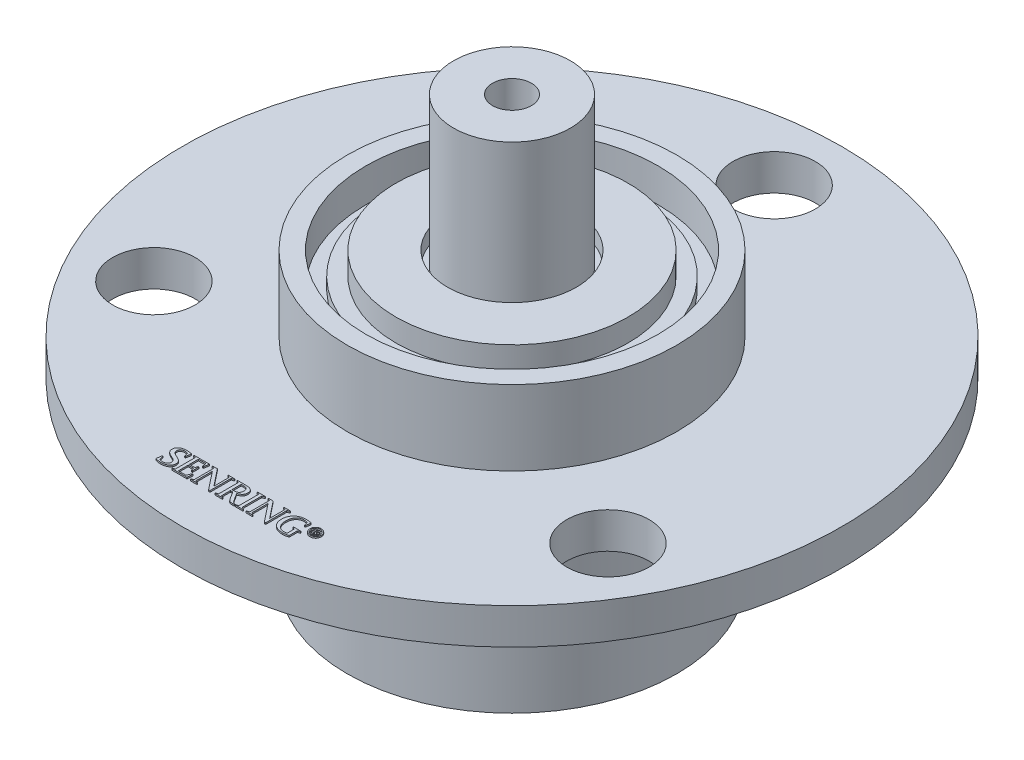
SolidWorks part; units mm, degrees
ref_plane "Front Plane" through (0, 0, 0) normal (0, 0, 1) x (1, 0, 0)
ref_plane "Top Plane" through (0, 0, 0) normal (0, 1, 0) x (1, 0, 0)
ref_plane "Right Plane" through (0, 0, 0) normal (1, 0, 0) x (0, 0, -1)
sketch "Sketch1" plane through (0, 0, 0) normal (0, 1, 0) x (1, 0, 0)
  circle A0 centre (0, 0) radius 22
  dimension "D1" = 44
extrude "Boss-Extrude1" add sketch "Sketch1" along normal blind 2.4
sketch "Sketch2" plane through (0, 2.4, 0) normal (0, 1, 0) x (1, 0, 0)
  circle A0 centre (0, 0) radius 11
  dimension "D1" = 22
extrude "Boss-Extrude2" add sketch "Sketch2" along normal blind 5
sketch "Sketch3" plane through (0, 0, 0) normal (0, -1, 0) x (1, 0, 0)
  circle A0 centre (0, 0) radius 11
  circle A1 centre (0, 0) radius 11 construction
extrude "Boss-Extrude3" add sketch "Sketch3" along normal blind 11.6
sketch "Sketch4" plane through (0, 2.4, 0) normal (0, 1, 0) x (1, 0, 0)
  circle A0 centre (0, 0) radius 17.5 construction
  circle A1 centre (0, 17.5) radius 2.75
  circle A2 centre (15.1554, -8.75) radius 2.75
  circle A3 centre (-15.1554, -8.75) radius 2.75
  point P5 (22, -7.5966)
  point P6 (0, 0)
  point P11 (0, 0)
  dimension "D1" = 35
  dimension "D2" = 5.5
  dimension "D3" = 3
extrude "Cut-Extrude1" cut sketch "Sketch4" against normal up to surface (2.4 mm away) up to face at (0, 0, -11)
sketch "Sketch5" plane through (0, 7.4, 0) normal (0, 1, 0) x (1, 0, 0)
  circle A0 centre (0, 0) radius 9.75
  circle A1 centre (0, 0) radius 7.75
  dimension "D1" = 19.5
  dimension "D2" = 15.5
extrude "Cut-Extrude2" cut sketch "Sketch5" against normal blind 1.5
sketch "Sketch6" plane through (0, 7.4, 0) normal (0, 1, 0) x (1, 0, 0)
  circle A0 centre (0, 0) radius 3.9
  dimension "D1" = 7.8
extrude "Boss-Extrude4" add sketch "Sketch6" along normal blind 9
sketch "Sketch7" plane through (0, 5.9, 0) normal (0, 1, 0) x (1, 0, 0)
  circle A0 centre (0, 0) radius 9.75
  circle A1 centre (0, 0) radius 9.75 construction
  circle A2 centre (0, 0) radius 8.75
  dimension "D1" = 17.5
extrude "Cut-Extrude3" cut sketch "Sketch7" against normal blind 0.75
sketch "Sketch8" plane through (0, 2.4, 0) normal (0, 1, 0) x (1, 0, 0)
  line L0 (0, 22) -> (0, -22) construction
  line L1 (-4.9, -18.25) -> (4.9, -18.25) construction
  line L2 (-4.9, -19.25) -> (4.9, -19.25) construction
  line L3 (-4.9, -19.25) -> (-4.9, -17.25) construction
  line L4 (-4.9, -17.25) -> (4.9, -17.25) construction
  line L5 (4.9, -19.25) -> (4.9, -17.25) construction
  line L6 (-4.9, -19.25) -> (4.9, -17.25) construction
  line L7 (-4.9, -17.25) -> (4.9, -19.25) construction
  circle A0 centre (0, 0) radius 22 construction
  text T0 "SENRING®" font "Constantia" height 1.5
  point P5 (0, -18.25)
  point P13 (0, 0)
  point P14 (-4.4275, -18.839)
  point P15 (0, 0)
  point P16 (0, 0)
  point P17 (0, 0)
  point P18 (0, 0)
  point P19 (0, 0)
  dimension "D1" = 2
  dimension "D2" = 9.8
  dimension "D3" = 2.75
extrude "Boss-Extrude5" add sketch "Sketch8" along normal blind 0.1
sketch "Sketch9" plane through (0, -11.6, 0) normal (0, -1, 0) x (1, 0, 0)
  circle A0 centre (0, 0) radius 9.4
  dimension "D1" = 18.8
extrude "Cut-Extrude4" cut sketch "Sketch9" against normal blind 0.3
sketch "Sketch10" plane through (0, -11.3, 0) normal (0, -1, 0) x (1, 0, 0)
  line L0 (0, 9.4) -> (0, -9.4) construction
  line L1 (-9.4, 0) -> (9.4, 0) construction
  line L2 (-9.2795, 1.5) -> (-6.9, 1.5)
  line L3 (-6.9, 1.5) -> (-6.9, -1.5)
  line L4 (-9.2795, -1.5) -> (-6.9, -1.5)
  line L5 (9.2795, 1.5) -> (6.9, 1.5)
  line L6 (6.9, 1.5) -> (6.9, -1.5)
  line L7 (9.2795, -1.5) -> (6.9, -1.5)
  circle A0 centre (0, 0) radius 9.4 construction
  circle A1 centre (0, 0) radius 9.4 construction
  arc A2 (-9.2795, 1.5) -> (-9.2795, -1.5) centre (0, 0) ccw
  arc A3 (9.2795, 1.5) -> (9.2795, -1.5) centre (0, 0) cw
  point P13 (-6.9, 0)
  point P15 (0, 0)
  dimension "D1" = 2.5
  dimension "D2" = 3
extrude "Cut-Extrude5" cut sketch "Sketch10" against normal blind 6
sketch "Sketch11" plane through (0, 16.4, 0) normal (0, 1, 0) x (1, 0, 0)
  circle A0 centre (0, 0) radius 1.3
  dimension "D1" = 2.6
extrude "Cut-Extrude6" cut sketch "Sketch11" against normal blind 3
sketch "Sketch12" plane through (0, 7.4, 0) normal (0, 1, 0) x (1, 0, 0)
  circle A0 centre (0, 0) radius 3.9
  circle A1 centre (0, 0) radius 3.9 construction
  circle A2 centre (0, 0) radius 4.3
  dimension "D1" = 0.4
extrude "Cut-Extrude7" cut sketch "Sketch12" against normal blind 1
